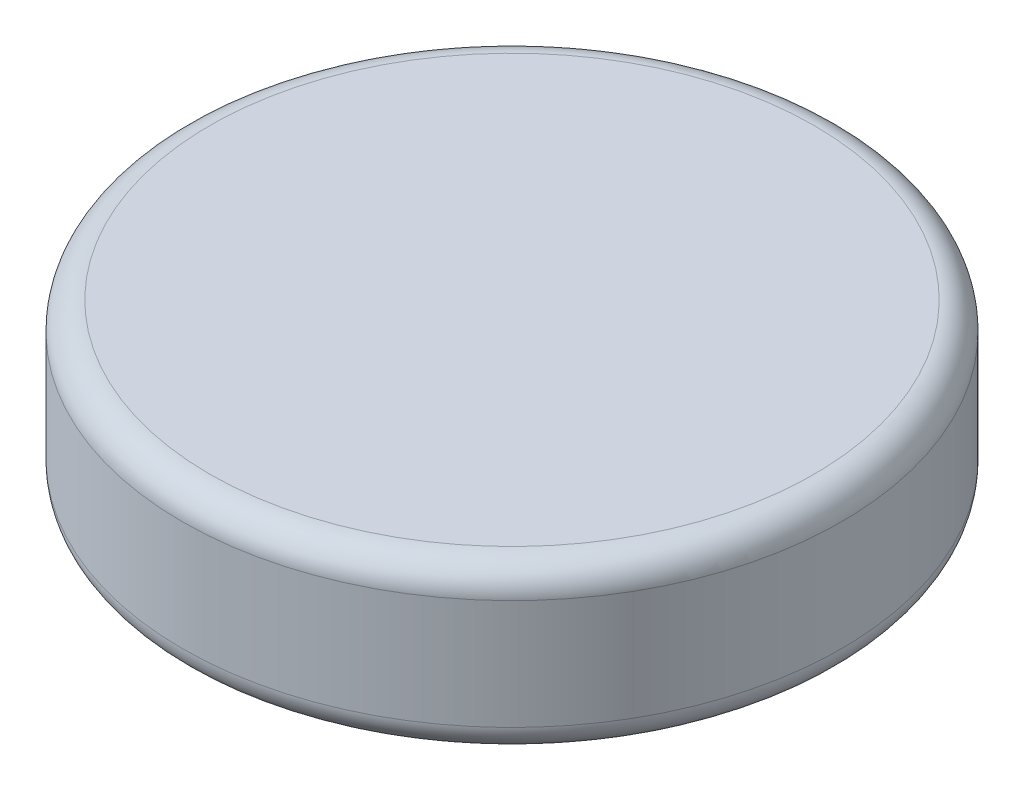
SolidWorks part; units mm, degrees
material "Nickel"
ref_plane "Front Plane" through (0, 0, 0) normal (0, 0, 1) x (1, 0, 0)
ref_plane "Top Plane" through (0, 0, 0) normal (0, 1, 0) x (1, 0, 0)
ref_plane "Right Plane" through (0, 0, 0) normal (1, 0, 0) x (0, 0, -1)
sketch "Sketch1" plane through (0, 0, 0) normal (0, 1, 0) x (1, 0, 0)
  circle A0 centre (0, 0) radius 6
  dimension "D1" = 12
extrude "Boss-Extrude1" add sketch "Sketch1" along normal blind 3
fillet "Fillet1" radius 0.5 2 edges at (0, 0, 6) (0, 3, 6)
